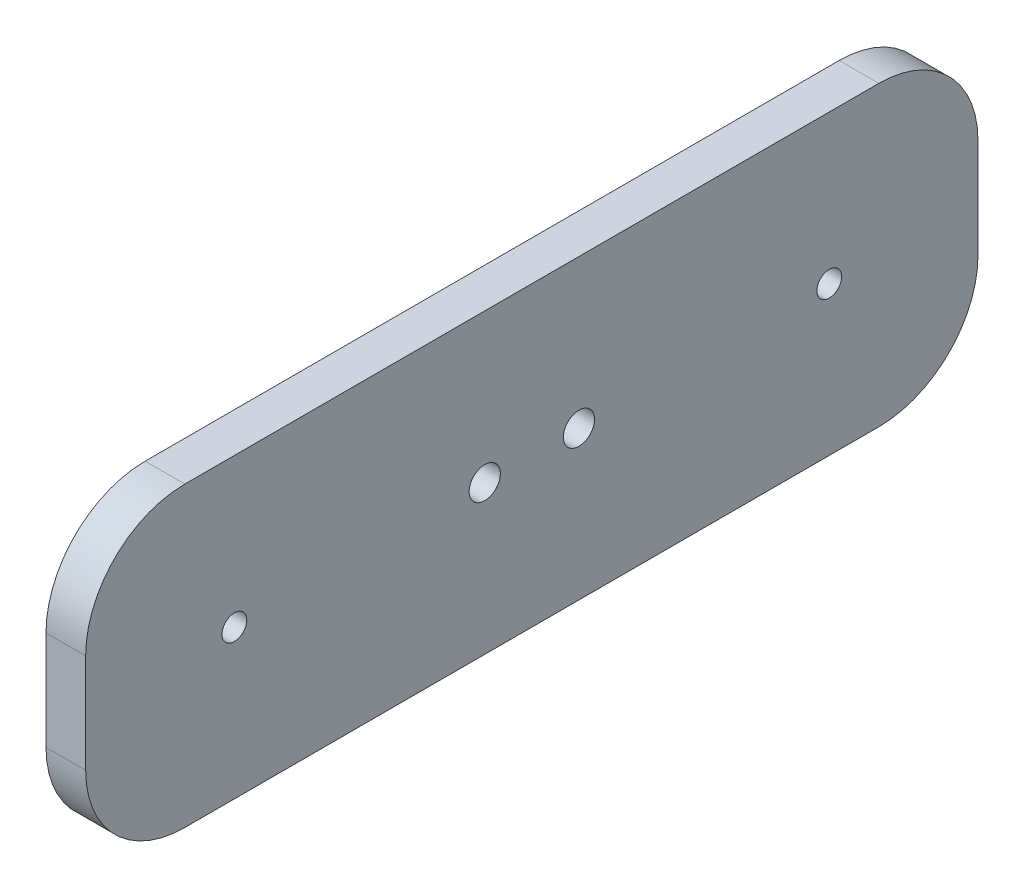
SolidWorks part; units mm, degrees
material "Du"
ref_plane "Front Plane" through (0, 0, 0) normal (0, 0, 1) x (1, 0, 0)
ref_plane "Top Plane" through (0, 0, 0) normal (0, 1, 0) x (1, 0, 0)
ref_plane "Right Plane" through (0, 0, 0) normal (1, 0, 0) x (0, 0, -1)
sketch "Sketch1" plane through (0, 0, 0) normal (1, 0, 0) x (0, 0, -1)
  line L1 (-45, -15) -> (45, -15)
  line L2 (-45, -15) -> (-45, 15)
  line L3 (-45, 15) -> (45, 15)
  line L4 (45, -15) -> (45, 15)
  line L5 (-45, -15) -> (45, 15) construction
  line L6 (-45, 15) -> (45, -15) construction
  point P0 (0, 0)
  dimension "D1" = 90
  dimension "D2" = 30
extrude "Boss-Extrude1" add sketch "Sketch1" along normal blind 4
sketch "Sketch6" plane through (4, 0, 0) normal (1, 0, 0) x (0, 0, -1)
  line L0 (2.2, 0) -> (-2.2, 0) construction
  circle A0 centre (-4.75, 0) radius 1.575
  dimension "D1" = 3.15
  dimension "D2" = 4.75
extrude "Cut-Extrude6" cut sketch "Sketch6" against normal through all
sketch "Sketch7" plane through (4, 0, 0) normal (1, 0, 0) x (0, 0, -1)
  line L0 (2.2, 0) -> (-2.2, 0) construction
  circle A0 centre (4.75, 0) radius 1.575
  dimension "D1" = 3.15
  dimension "D2" = 4.75
extrude "Cut-Extrude7" cut sketch "Sketch7" against normal through all
sketch "Sketch13" plane through (4, 0, 0) normal (1, 0, 0) x (0, 0, -1)
  line L0 (2.2, 0) -> (-2.2, 0) construction
  line L1 (-45, 15) -> (-45, -15) construction
  circle A0 centre (-30, 0) radius 1.25
  dimension "D1" = 2.5
  dimension "D2" = 15
extrude "Cut-Extrude13" cut sketch "Sketch13" against normal through all
sketch "Sketch14" plane through (4, 0, 0) normal (1, 0, 0) x (0, 0, -1)
  line L0 (2.2, 0) -> (-2.2, 0) construction
  line L1 (45, -15) -> (45, 15) construction
  circle A0 centre (30, 0) radius 1.25
  dimension "D1" = 2.5
  dimension "D2" = 15
extrude "Cut-Extrude14" cut sketch "Sketch14" against normal through all
fillet "Fillet1" radius 10 4 edges at (2, 15, 45) (2, -15, 45) (2, 15, -45) (2, -15, -45)
sketch "Sketch16" plane through (0, 0, 0) normal (-1, 0, 0) x (0, 0, 1)
